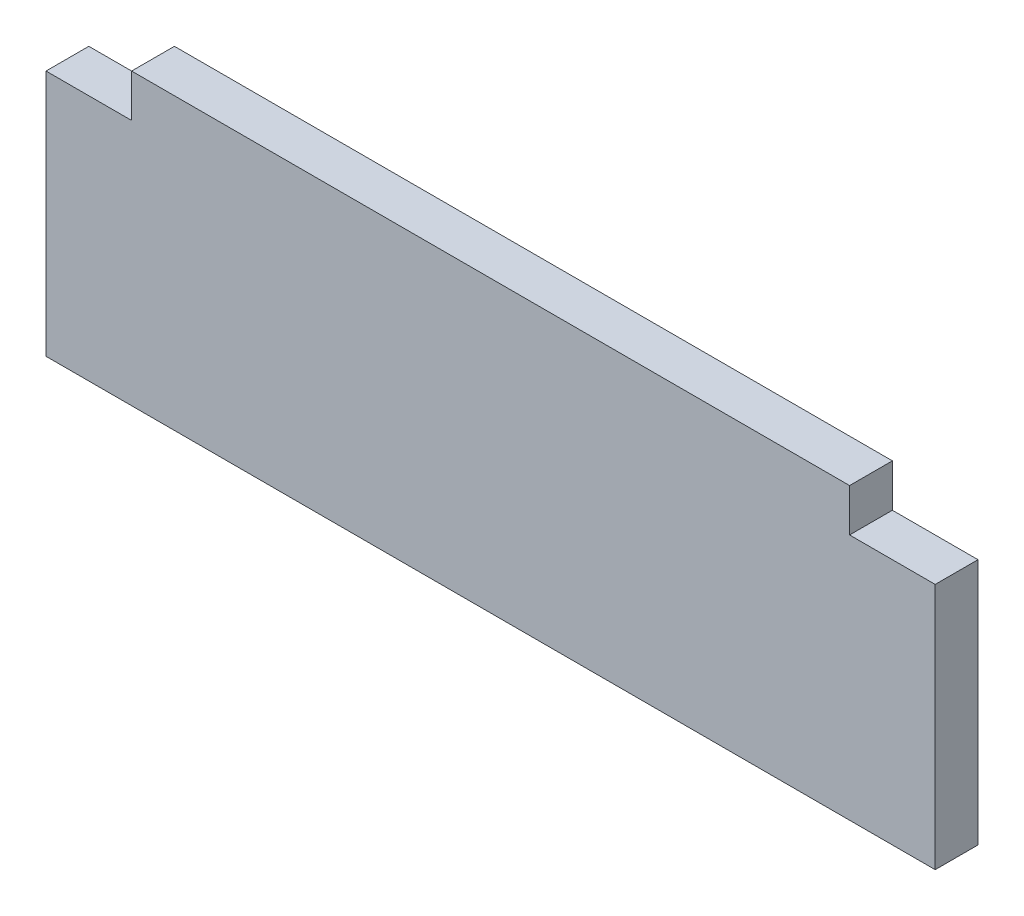
SolidWorks part; units mm, degrees
material "Acrylic (Medium-high impact)"
ref_plane "Front Plane" through (0, 0, 0) normal (0, 0, 1) x (1, 0, 0)
ref_plane "Top Plane" through (0, 0, 0) normal (0, 1, 0) x (1, 0, 0)
ref_plane "Right Plane" through (0, 0, 0) normal (1, 0, 0) x (0, 0, -1)
sketch "Sketch1" plane through (0, 0, 0) normal (0, 0, 1) x (1, 0, 0)
  line L1 (-65.95, 21.5) -> (65.95, 21.5)
  line L2 (-65.95, 21.5) -> (-65.95, -21.5)
  line L3 (-65.95, -21.5) -> (65.95, -21.5)
  line L4 (65.95, 21.5) -> (65.95, -21.5)
  line L5 (-65.95, 21.5) -> (65.95, -21.5) construction
  line L6 (-65.95, -21.5) -> (65.95, 21.5) construction
  point P0 (0, 0)
  dimension "D1" = 43
  dimension "D2" = 131.9
extrude "Boss-Extrude1" add sketch "Sketch1" along normal mid plane 6.35
sketch "Sketch2" plane through (0, 0, 3.175) normal (0, 0, 1) x (1, 0, 0)
  line L1 (-65.95, 21.5) -> (-53.25, 21.5)
  line L2 (-65.95, 21.5) -> (-65.95, 15.15)
  line L3 (-65.95, 15.15) -> (-53.25, 15.15)
  line L4 (-53.25, 21.5) -> (-53.25, 15.15)
  dimension "D1" = 6.35
  dimension "D2" = 12.7
extrude "Cut-Extrude1" cut sketch "Sketch2" against normal through all
mirror "Mirror1" about plane through (0, 0, 0) normal (1, 0, 0) of "Cut-Extrude1"
sketch "Sketch3" [suppressed] plane through (0, 0, -3.175) normal (0, 0, -1) x (-1, 0, 0)
  line L0 (120.496, 21.5) -> (120.496, -1.36)
  line L1 (133.45, 21.5) -> (-133.45, 21.5) construction
  line L2 (102.716, -1.36) -> (102.716, 21.5)
  line L3 (102.716, 21.5) -> (120.496, 21.5)
  line L5 (146.15, 15.15) -> (146.15, -21.5) construction
  line L6 (68.7658, 21.5) -> (68.7658, -1.36)
  line L7 (50.9858, -1.36) -> (50.9858, 21.5)
  line L8 (50.9858, 21.5) -> (68.7658, 21.5)
  line L9 (-51.9989, 21.5) -> (-51.9989, -0.344)
  line L10 (46.0451, 21.5) -> (35.8851, 21.5)
  line L11 (46.0451, 21.5) -> (46.0451, -8.98)
  line L12 (46.0451, -8.98) -> (35.8851, -8.98)
  line L13 (35.8851, 21.5) -> (35.8851, -8.98)
  line L14 (31.3131, 21.5) -> (-48.6969, 21.5)
  line L15 (31.3131, 21.5) -> (31.3131, -8.98)
  line L16 (31.3131, -8.98) -> (-48.6969, -8.98)
  line L17 (-48.6969, 21.5) -> (-48.6969, -8.98)
  line L18 (-69.0169, -0.344) -> (-69.0169, 21.5)
  line L19 (-69.0169, 21.5) -> (-51.9989, 21.5)
  line L20 (-103.5489, 21.5) -> (-103.5489, -0.09)
  line L21 (-84.2569, 21.5) -> (-99.4969, 21.5)
  line L22 (-84.2569, 21.5) -> (-84.2569, -8.98)
  line L23 (-84.2569, -8.98) -> (-99.4969, -8.98)
  line L24 (-99.4969, 21.5) -> (-99.4969, -8.98)
  line L25 (-120.0193, -0.09) -> (-120.0193, 21.5)
  line L26 (-120.0193, 21.5) -> (-103.5489, 21.5)
  arc A0 (120.496, -1.36) -> (102.716, -1.36) centre (111.606, -1.36) cw
  arc A1 (68.7658, -1.36) -> (50.9858, -1.36) centre (59.8758, -1.36) cw
  arc A2 (-51.9989, -0.344) -> (-69.0169, -0.344) centre (-60.5079, -0.344) cw
  arc A3 (-103.5489, -0.09) -> (-120.0193, -0.09) centre (-111.7841, -0.09) cw
  dimension "D1" = 25.654
  dimension "D2" = 17.78
  dimension "D3" = 22.86
  dimension "D4" = 22.86
  dimension "D5" = 17.78
  dimension "D6" = 33.9502
  dimension "D7" = 30.48
  dimension "D8" = 4.9408
  dimension "D9" = 10.16
  dimension "D10" = 4.572
  dimension "D11" = 80.01
  dimension "D12" = 3.302
  dimension "D13" = 21.844
  dimension "D14" = 17.018
  dimension "D15" = 15.24
  dimension "D16" = 15.24
  dimension "D17" = 4.0519
  dimension "D18" = 16.4704
  dimension "D19" = 21.59
extrude "Cut-Extrude2" [suppressed] cut sketch "Sketch3" against normal through all
equation "\"box_width\" = 305mm"
equation "\"box_other_width\" = 170mm"
equation "\"box_height\" = 43mm"
equation "\"D1@Sketch1\"=\"box_height\""
equation "\"D2@Sketch1\"=\"side_length\""
equation "\"side_length\"= \"box_other_width\" - 1.5in"
